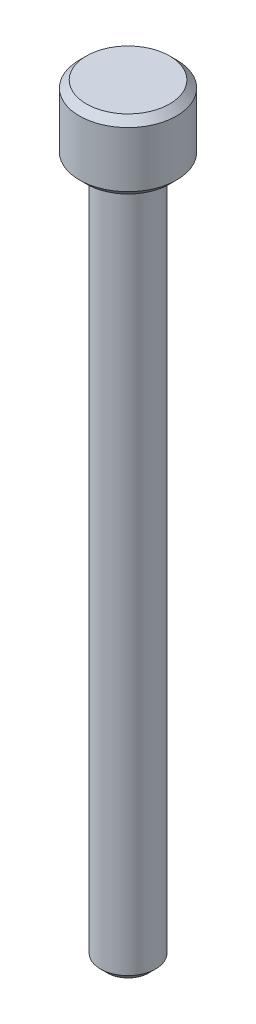
SolidWorks part; units mm, degrees
ref_plane "Front Plane" through (0, 0, 0) normal (0, 0, 1) x (1, 0, 0)
ref_plane "Top Plane" through (0, 0, 0) normal (0, 1, 0) x (1, 0, 0)
ref_plane "Right Plane" through (0, 0, 0) normal (1, 0, 0) x (0, 0, -1)
sketch "Sketch1" plane through (0, 0, 0) normal (0, 0, 1) x (1, 0, 0)
  line L0 (0, 0) -> (0, 28.3679) construction
  line L1 (3.9687, 99) -> (3.9688, 1)
  line L2 (2.9688, 0) -> (0, 0)
  line L3 (4.9687, 100) -> (6, 100)
  line L4 (7, 101) -> (7, 109)
  line L5 (6, 110) -> (0, 110)
  line L6 (0, 110) -> (0, 0)
  line L7 (7, 109) -> (6, 110)
  line L8 (6, 100) -> (7, 101)
  line L9 (4.9687, 100) -> (3.9687, 99)
  line L10 (3.9688, 1) -> (2.9688, 0)
  point P3 (3.9687, 100)
  point P4 (3.9688, 0)
  point P6 (7, 100)
  point P7 (7, 110)
  dimension "D1" = 3.9688
  dimension "D2" = 1
  dimension "D3" = 45
  dimension "D4" = 1
  dimension "D5" = 45
  dimension "D6" = 1
  dimension "D7" = 45
  dimension "D8" = 1
  dimension "D9" = 45
revolve "Revolve1" add sketch "Sketch1" angle 360 about L0
